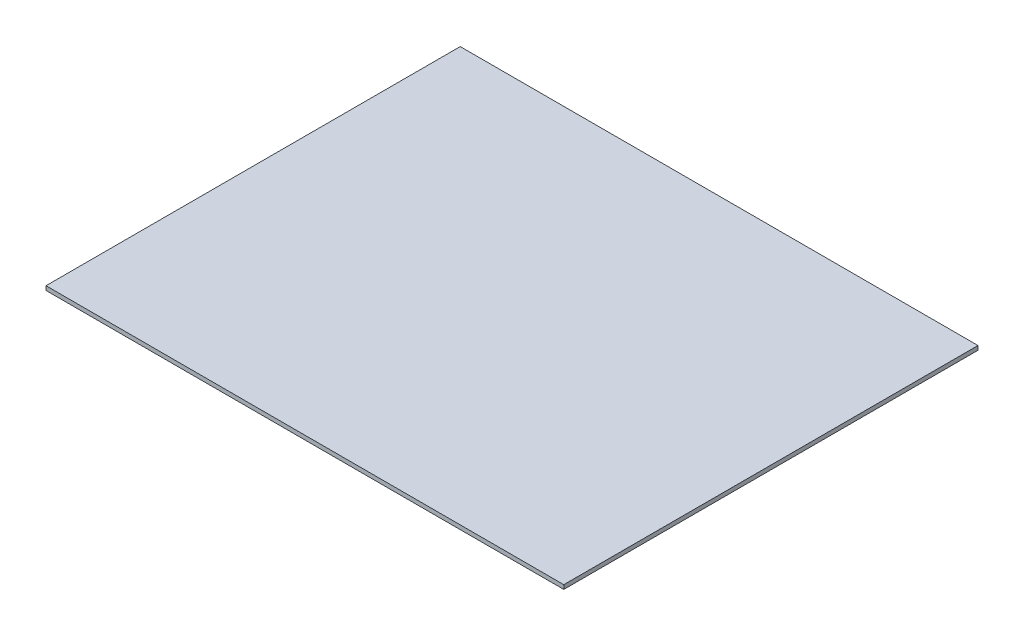
SolidWorks part; units mm, degrees
material "Acrylic (Medium-high impact)"
ref_plane "Front Plane" through (0, 0, 0) normal (0, 0, 1) x (1, 0, 0)
ref_plane "Top Plane" through (0, 0, 0) normal (0, 1, 0) x (1, 0, 0)
ref_plane "Right Plane" through (0, 0, 0) normal (1, 0, 0) x (0, 0, -1)
sketch "Sketch1" plane through (0, 0, 0) normal (0, 1, 0) x (1, 0, 0)
  line L1 (-127, -101.6) -> (127, -101.6)
  line L2 (-127, -101.6) -> (-127, 101.6)
  line L3 (-127, 101.6) -> (127, 101.6)
  line L4 (127, -101.6) -> (127, 101.6)
  line L5 (-127, -101.6) -> (127, 101.6) construction
  line L6 (-127, 101.6) -> (127, -101.6) construction
  point P0 (0, 0)
  dimension "D1" = 203.2
  dimension "D2" = 254
extrude "Boss-Extrude1" add sketch "Sketch1" along normal blind 2.032
